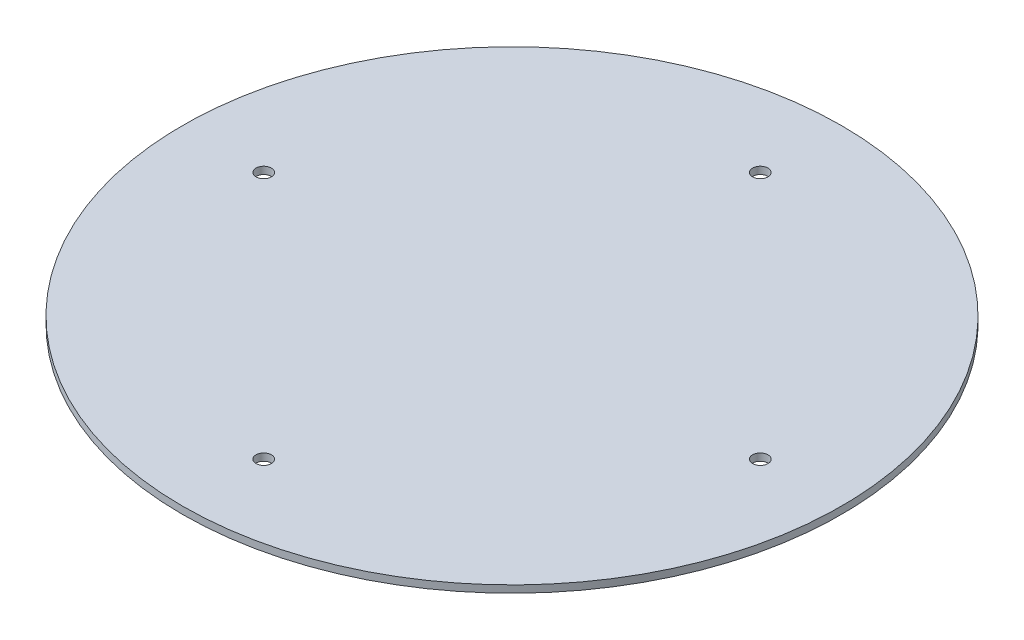
SolidWorks part; units mm, degrees
material "E-Glass Fiber"
ref_plane "Front Plane" through (0, 0, 0) normal (0, 0, 1) x (1, 0, 0)
ref_plane "Top Plane" through (0, 0, 0) normal (0, 1, 0) x (1, 0, 0)
ref_plane "Right Plane" through (0, 0, 0) normal (1, 0, 0) x (0, 0, -1)
sketch "Sketch1" plane through (0, 0, 0) normal (0, 1, 0) x (1, 0, 0)
  arc A0 (-65, -33.2265) -> (-33.2265, -65) centre (0, 0) ccw
  arc A1 (-65, 33.2265) -> (-65, -33.2265) centre (0, 0) ccw construction
  arc A2 (33.2265, 65) -> (-33.2265, 65) centre (0, 0) ccw construction
  arc A3 (-33.2265, 65) -> (-65, 33.2265) centre (0, 0) ccw
  arc A4 (65, -33.2265) -> (65, 33.2265) centre (0, 0) ccw construction
  arc A5 (65, 33.2265) -> (33.2265, 65) centre (0, 0) ccw
  arc A6 (-33.2265, -65) -> (33.2265, -65) centre (0, 0) ccw construction
  arc A7 (33.2265, -65) -> (65, -33.2265) centre (0, 0) ccw
  circle A8 centre (0, 0) radius 73
  point P14 (0, 0)
  dimension "D1" = 146
extrude "Boss-Extrude1" add sketch "Sketch1" along normal blind 1.6 contours A7 A8 A5 A3 A0
sketch "Sketch2" plane through (0, 1.6, 0) normal (0, 1, 0) x (1, 0, 0)
  line L0 (0, 0) -> (0, 55) construction
  line L3 (0, 0) -> (55, 0) construction
  line L4 (0, 0) -> (0, -55) construction
  line L6 (-55, 0) -> (0, 0) construction
  point P0 (0, 55)
  point P2 (55, 0)
  point P4 (-55, 0)
  point P6 (0, -55)
  dimension "D1" = 55
hole_wizard "M3 Clearance Hole1" positions "Sketch2" profile "Sketch3" hole size "M3" standard "ISO" end condition through all
sketch "Sketch3" plane through (0, 1.6, -55) normal (1, 0, 0) x (0, 0, 1)
  line L0 (0, 0) -> (0, 1.6)
  line L1 (0, 1.6) -> (1.7, 1.6)
  line L2 (1.7, 1.6) -> (1.7, 0)
  line L5 (1.7, 0) -> (0, 0)
  line L11 (0, -6.35) -> (0, 107.95) construction
  dimension "Thru Hole Dia." = 3.4
  dimension "Thru Hole Depth" = 1.6
